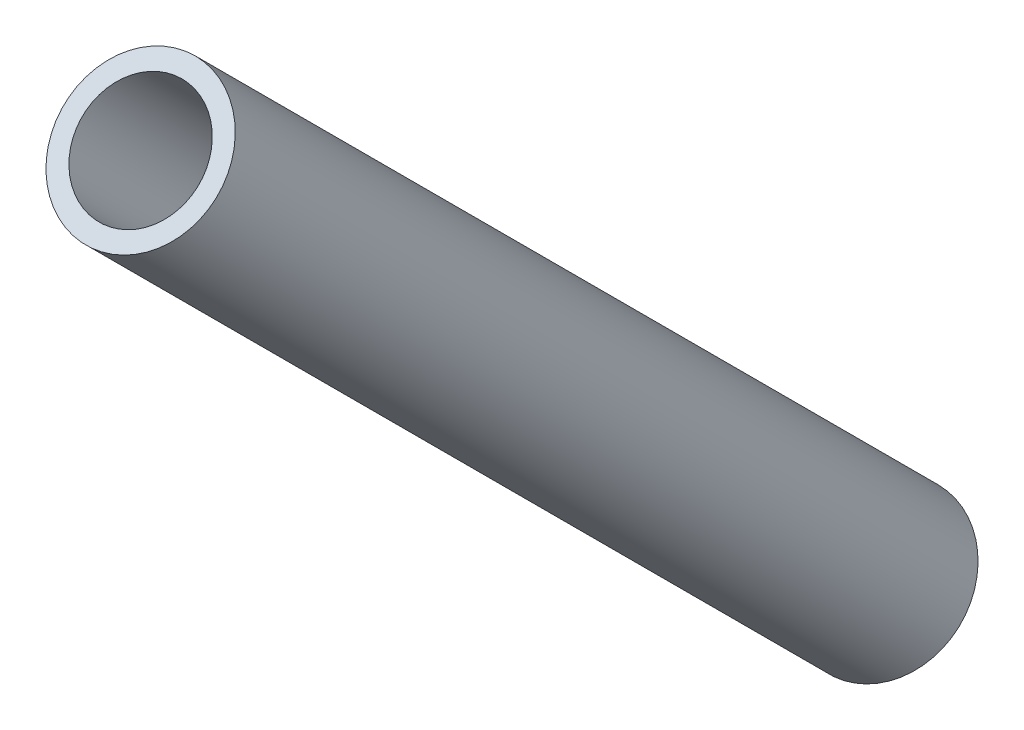
SolidWorks part; units mm, degrees
material "ABS"
ref_plane "Front Plane" through (0, 0, 0) normal (0, 0, 1) x (1, 0, 0)
ref_plane "Top Plane" through (0, 0, 0) normal (0, 1, 0) x (1, 0, 0)
ref_plane "Right Plane" through (0, 0, 0) normal (1, 0, 0) x (0, 0, -1)
sketch "Sketch6" plane through (0, 0, 0) normal (1, 0, 0) x (0, 0, -1)
  line L0 (0, 0) -> (31.026, 31.026) construction
  line L1 (0, 0) -> (35.3089, 0) construction
  dimension "D1" = 45
sketch3d "3DSketch2"
  line L0 (0, 0, 0) -> (0, 31.026, -31.026) construction
sketch "Sketch9" plane through (0, 0, 0) normal (0, 0.7071, 0.7071) x (1, 0, 0)
  circle A0 centre (0, 0) radius 13.081
  dimension "D1" = 26.162
extrude "Boss-Extrude2" add sketch "Sketch9" along normal blind 177.8 separate body
sketch "Sketch3" plane through (0, 429.2472, -177.8) normal (0, -0.7071, -0.7071) x (1, 0, 0)
  circle A0 centre (0, 429.2472) radius 9.906
  dimension "D1" = 19.812
extrude "Cut-Extrude1" cut sketch "Sketch3" along normal blind 171.45
sketch "Sketch5" plane through (0, 52.0764, -52.0764) normal (0, -0.7071, -0.7071) x (-1, 0, 0)
  line L0 (0, 2.4214) -> (0, -1.4828) construction
  line L1 (-1.524, -64.9477) -> (1.524, -64.9477)
  line L6 (1.524, -64.9477) -> (1.524, -68.8678)
  line L7 (-1.524, -64.9477) -> (-1.524, -68.8678)
  line L8 (0, -68.6307) -> (3.1083, -68.6307) construction
  line L9 (0, -73.6472) -> (7.3112, -73.6472) construction
  line L10 (-1.524, -82.3467) -> (1.524, -82.3467)
  line L11 (-1.524, -82.3467) -> (-1.524, -78.4266)
  line L12 (1.524, -82.3467) -> (1.524, -78.4266)
  arc A2 (1.524, -78.4266) -> (1.524, -68.8678) centre (0, -73.6472) ccw
  arc A3 (-1.524, -68.8678) -> (-1.524, -78.4266) centre (0, -73.6472) ccw
  point P13 (0, -8.1915)
  point P17 (0, -64.9477)
  dimension "D3" = 10.033
  dimension "D1" = 1.524
  dimension "D2" = 3.683
extrude "Cut-Extrude2" cut sketch "Sketch5" against normal through all
